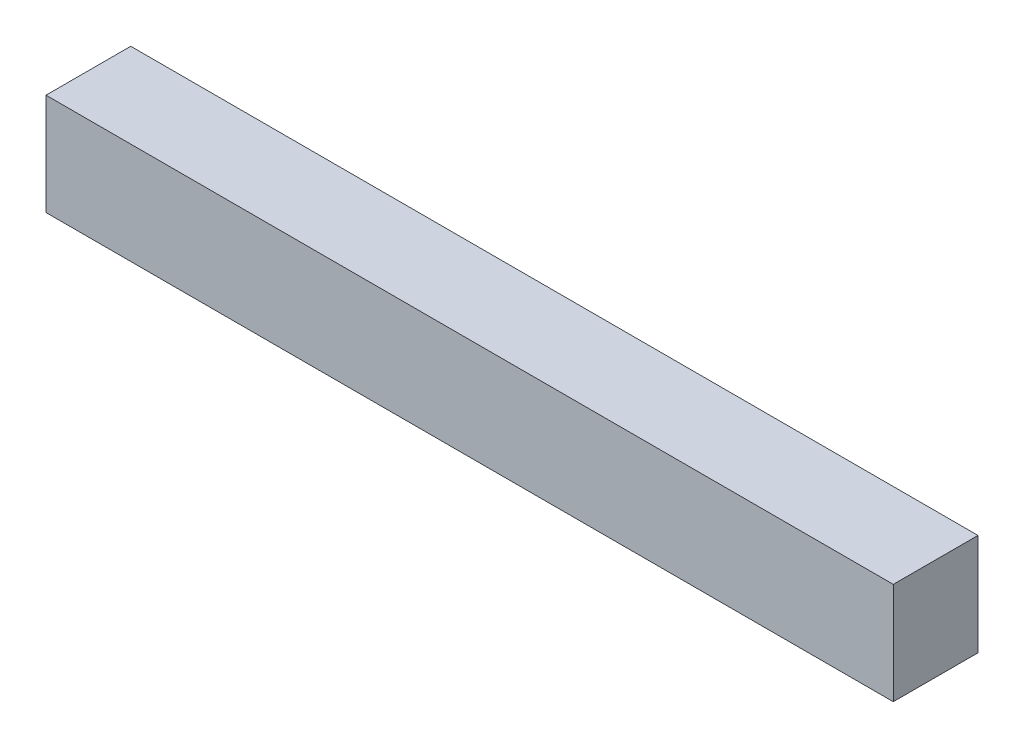
SolidWorks part; units mm, degrees
ref_plane "Front Plane" through (0, 0, 0) normal (0, 0, 1) x (1, 0, 0)
ref_plane "Top Plane" through (0, 0, 0) normal (0, 1, 0) x (1, 0, 0)
ref_plane "Right Plane" through (0, 0, 0) normal (1, 0, 0) x (0, 0, -1)
sketch "Sketch1" plane through (0, 0, 0) normal (0, 1, 0) x (1, 0, 0)
  line L1 (-25, 2.5) -> (25, 2.5)
  line L2 (-25, 2.5) -> (-25, -2.5)
  line L3 (-25, -2.5) -> (25, -2.5)
  line L4 (25, 2.5) -> (25, -2.5)
  line L5 (-25, 2.5) -> (25, -2.5) construction
  line L6 (-25, -2.5) -> (25, 2.5) construction
  point P0 (0, 0)
  dimension "D1" = 5
  dimension "D2" = 50
extrude "Boss-Extrude1" add sketch "Sketch1" along normal blind 6
